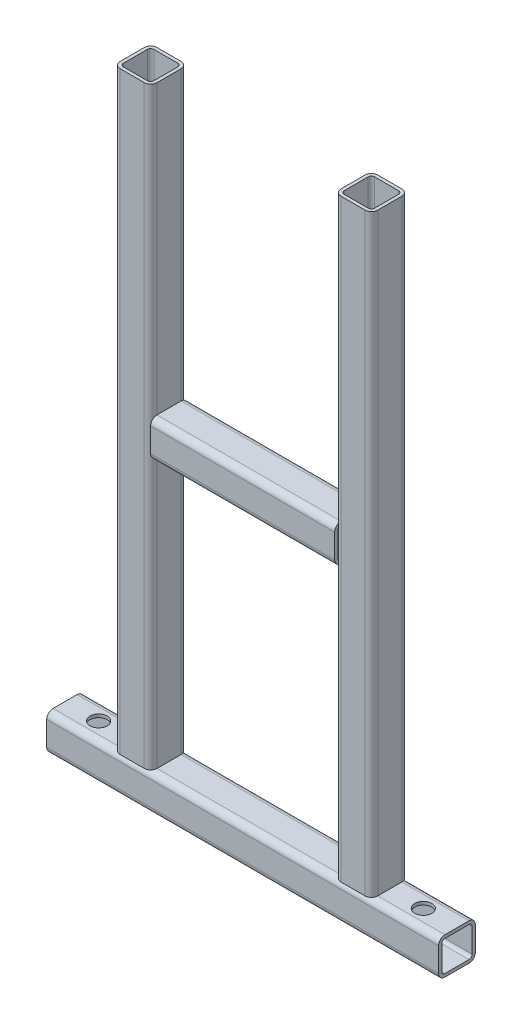
SolidWorks part; units mm, degrees
material "AISI 304"
ref_plane "Ön Düzlem" through (0, 0, 0) normal (0, 0, 1) x (1, 0, 0)
ref_plane "Üst Düzlem" through (0, 0, 0) normal (0, 1, 0) x (1, 0, 0)
ref_plane "Sağ Düzlem" through (0, 0, 0) normal (1, 0, 0) x (0, 0, -1)
sketch "Çizim1" plane through (0, 0, 0) normal (0, 0, 1) x (1, 0, 0)
  line L1 (0, 0) -> (0, -27.4203) construction
  line L2 (-90.13, 0) -> (-90.13, -500)
  line L3 (90.13, 0) -> (90.13, -500)
  line L4 (-160, -500) -> (160, -500)
  line L5 (-90.13, -250) -> (90.13, -250)
  line L6 (0, -27.4203) -> (0, -551.4171) construction
  point P4 (0, 0)
  point P12 (0, -500)
  point P15 (0, -500)
  dimension "D1" = 180.26
  dimension "D2" = 500
  dimension "D3" = 320
other "Square tube - configured 30 X 30 X 2.6(1)"
ref_plane "Düzlem1" through (-90.13, 0, 0) normal (0, -1, 0) x (1, 0, 0)
sketch "Sketch1" plane through (-90.13, 0, 0) normal (0, -1, 0) x (1, 0, 0)
  line L0 (-9.8, -12.4) -> (9.8, -12.4)
  line L1 (-12.4, -9.8) -> (-12.4, 9.8)
  line L2 (9.8, 12.4) -> (-9.8, 12.4)
  line L3 (12.4, 9.8) -> (12.4, -9.8)
  line L4 (-9.8, -15) -> (9.8, -15)
  line L5 (-15, -9.8) -> (-15, 9.8)
  line L6 (9.8, 15) -> (-9.8, 15)
  line L7 (15, 9.8) -> (15, -9.8)
  arc A0 (15, 9.8) -> (9.8, 15) centre (9.8, 9.8) ccw
  arc A1 (9.8, -15) -> (15, -9.8) centre (9.8, -9.8) ccw
  arc A2 (-15, -9.8) -> (-9.8, -15) centre (-9.8, -9.8) ccw
  arc A3 (-9.8, 15) -> (-15, 9.8) centre (-9.8, 9.8) ccw
  arc A4 (-9.8, 12.4) -> (-12.4, 9.8) centre (-9.8, 9.8) ccw
  arc A5 (12.4, 9.8) -> (9.8, 12.4) centre (9.8, 9.8) ccw
  arc A6 (9.8, -12.4) -> (12.4, -9.8) centre (9.8, -9.8) ccw
  arc A7 (-12.4, -9.8) -> (-9.8, -12.4) centre (-9.8, -9.8) ccw
  point P0 (-15, 0)
  point P1 (15, 0)
  point P2 (0, 15)
  point P3 (0, -15)
  point P4 (0, 0)
  point P5 (-15, -15)
  point P6 (15, -15)
  point P7 (15, 15)
  point P8 (-15, 15)
  point P33 (0, 0)
  dimension "D1" = 5.2
  dimension "Thickness" = 2.6
  dimension "V_leg" = 30
sketch "Çizim7" plane through (0, -485, 0) normal (0, 1, 0) x (1, 0, 0)
  line L0 (-160, 0) -> (-105.13, 0) construction
  line L1 (-160, 9.8) -> (-160, -9.8) construction
  line L2 (-105.13, -9.8) -> (-105.13, 9.8) construction
hole_wizard "M16 Dişli Delik1" positions "Çizim8" profile "Çizim9" tap size "M16" standard "ISO" end condition through all
sketch "Çizim8" plane through (0, -485, 0) normal (0, 1, 0) x (1, 0, 0)
  line L0 (-160, 0) -> (-105.13, 0) construction
  point P0 (-132.565, 0)
sketch "Çizim9" plane through (-132.565, -485, 0) normal (1, 0, 0) x (0, 0, 1)
  line L0 (0, 0) -> (0, 30)
  line L1 (0, 30) -> (7, 30)
  line L2 (7, 30) -> (7, 0)
  line L5 (7, 0) -> (0, 0)
  line L11 (0, -6.35) -> (0, 107.95) construction
  dimension "Thru Tap Drill Dia." = 14
  dimension "Thru Tap Drill Depth" = 30
cosmetic thread "Delik Dişi1"
mirror "Aynalama1" about plane through (0, 0, 0) normal (1, 0, 0) of "M16 Dişli Delik1"
cosmetic thread "Delik Dişi2"
